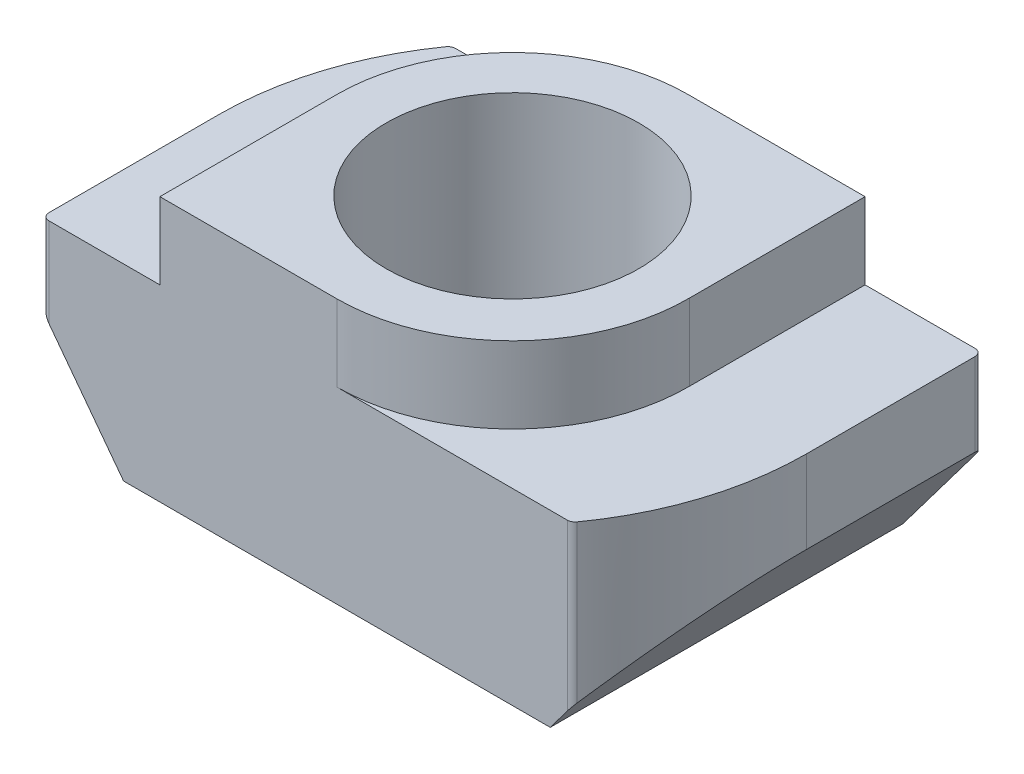
SolidWorks part; units mm, degrees
ref_plane "前视基准面" through (0, 0, 0) normal (0, 0, 1) x (1, 0, 0)
ref_plane "上视基准面" through (0, 0, 0) normal (0, 1, 0) x (1, 0, 0)
ref_plane "右视基准面" through (0, 0, 0) normal (1, 0, 0) x (0, 0, -1)
sketch "草图1" plane through (0, 0, 0) normal (0, 1, 0) x (1, 0, 0)
  line L0 (-6.3587, 0) -> (6.7929, 0) construction
  line L1 (3.92, -3.0123) -> (-4.9005, -3.0123)
  line L2 (4.9795, 0) -> (4.9795, 2.8677)
  line L3 (4.8595, 2.9877) -> (-3.9786, 2.9877)
  line L4 (-5.0205, -2.8923) -> (-5.0205, 0)
  line L6 (4.9795, 2.9877) -> (-5.0205, -3.0123) construction
  line L7 (0, 4.2946) -> (0, -4.2424) construction
  arc A0 (4.0297, -2.956) -> (4.9795, 0) centre (-0.0955, 0) ccw
  arc A1 (4.0297, -2.956) -> (3.92, -3.0123) centre (3.92, -2.8773) cw
  arc A2 (-5.0205, 0) -> (-4.0889, 2.9306) centre (0.0545, 0) cw
  arc A3 (-4.0889, 2.9306) -> (-3.9786, 2.9877) centre (-3.9786, 2.8527) cw
  arc A4 (4.9795, 2.8677) -> (4.8595, 2.9877) centre (4.8595, 2.8677) ccw
  arc A5 (-4.9005, -3.0123) -> (-5.0205, -2.8923) centre (-4.9005, -2.8923) cw
  point P0 (0, 0)
  dimension "D3" = 5.075
  dimension "D4" = 0.135
  dimension "D6" = 5.075
  dimension "D7" = 0.135
  dimension "D8" = 0.12
  dimension "D1" = 10
  dimension "D2" = 6
  dimension "D5" = 3.92
extrude "凸台-拉伸1" add sketch "草图1" along normal blind 3.2
sketch "草图2" plane through (0, 3.2, 0) normal (0, 1, 0) x (1, 0, 0)
  line L1 (0, -3.0123) -> (-3.0123, -3.0123)
  line L2 (2.9877, 0) -> (2.9877, 2.9877)
  line L3 (2.9877, 2.9877) -> (0, 2.9877)
  line L4 (-3.0123, -3.0123) -> (-3.0123, 0)
  line L5 (-4.9005, -3.0123) -> (3.92, -3.0123) construction
  line L6 (2.9877, 2.9877) -> (-3.0123, -3.0123) construction
  line L7 (-6.3112, 0) -> (6.4517, 0) construction
  line L8 (0, -3.8745) -> (0, 3.6707) construction
  line L9 (4.8595, 2.9877) -> (-3.9786, 2.9877) construction
  arc A0 (-3.0123, 0) -> (0, 2.9877) centre (-0.0246, 0) cw
  arc A1 (0, -3.0123) -> (2.9877, 0) centre (0, -0.0246) ccw
  point P0 (0, 0)
  dimension "D1" = 6
extrude "凸台-拉伸2" add sketch "草图2" along normal blind 1.3
sketch "草图3" plane through (0, 0, 0) normal (0, 0, 1) x (1, 0, 0)
  line L0 (5.0205, 0) -> (3.63, 0)
  line L1 (-4.9005, 0) -> (3.92, 0) construction
  line L2 (-3.63, 0) -> (-5.0205, 1.8453)
  line L3 (-5.0205, 3.2) -> (-5.0205, 0) construction
  line L4 (0, -1.7084) -> (0, 1.9848) construction
  line L5 (-5.0205, 1.8453) -> (-5.0205, 0)
  line L6 (-5.0205, 0) -> (-3.63, 0)
  line L7 (5.0205, 1.8453) -> (5.0205, 0)
  line L8 (3.63, 0) -> (5.0205, 1.8453)
  dimension "D1" = 7.26
  dimension "D2" = 53
extrude "切除-拉伸1" cut sketch "草图3" against normal mid plane 9.3
sketch "草图4" plane through (0, 4.5, 0) normal (0, 1, 0) x (1, 0, 0)
  circle A0 centre (-0.0246, 0) radius 2.15
  dimension "D1" = 4.3
extrude "切除-拉伸2" cut sketch "草图4" against normal up to next
cosmetic thread "装饰螺纹线1"
sketch "草图5" [suppressed] plane through (0, 0, 0) normal (0, 1, 0) x (1, 0, 0)
  line L0 (-7.0636, 0) -> (6.9703, 0) construction
  line L1 (3.7417, -3) -> (-4.5, -3)
  line L2 (5, 0) -> (5, 2.5)
  line L3 (4.5, 3) -> (-3.7417, 3)
  line L4 (-5, -2.5) -> (-5, 0)
  line L6 (5, 3) -> (-5, -3) construction
  line L7 (0, 4.4385) -> (0, -4.2975) construction
  arc A0 (4.1574, -2.7778) -> (5, 0) centre (0, 0) ccw
  arc A1 (4.1574, -2.7778) -> (3.7417, -3) centre (3.7417, -2.5) cw
  arc A2 (-5, 0) -> (-4.1574, 2.7778) centre (0, 0) cw
  arc A3 (-4.1574, 2.7778) -> (-3.7417, 3) centre (-3.7417, 2.5) cw
  arc A4 (5, 2.5) -> (4.5, 3) centre (4.5, 2.5) ccw
  arc A5 (-4.5, -3) -> (-5, -2.5) centre (-4.5, -2.5) cw
  point P0 (0, 0)
  dimension "D3" = 5
  dimension "D4" = 0.5
  dimension "D5" = 5
  dimension "D6" = 0.5
  dimension "D7" = 0.5
  dimension "D1" = 10
  dimension "D2" = 6
extrude "凸台-拉伸3" [suppressed] add sketch "草图5" along normal blind 3.2
sketch "草图6" [suppressed] plane through (0, 3.2, 0) normal (0, 1, 0) x (1, 0, 0)
  line L1 (0, -3) -> (-3, -3)
  line L2 (3, 0) -> (3, 3)
  line L3 (3, 3) -> (0, 3)
  line L4 (-3, -3) -> (-3, 0)
  line L5 (4.5, 3) -> (-3.7417, 3) construction
  line L6 (3, 3) -> (-3, -3) construction
  line L7 (-3.3629, 0) -> (3.4229, 0) construction
  line L8 (0, 3.4409) -> (0, -3.4409) construction
  line L9 (-4.5, -3) -> (3.7417, -3) construction
  arc A0 (-3, 0) -> (0, 3) centre (0, 0) cw
  arc A1 (0, -3) -> (3, 0) centre (0, 0) ccw
  point P0 (0, 0)
  dimension "D1" = 6
extrude "凸台-拉伸4" [suppressed] add sketch "草图6" along normal blind 1.3
sketch "草图7" [suppressed] plane through (0, 4.5, 0) normal (0, 1, 0) x (1, 0, 0)
  circle A0 centre (0, 0) radius 1.72
  dimension "D1" = 4.3
extrude "切除-拉伸3" [suppressed] cut sketch "草图7" against normal up to next
cosmetic thread "装饰螺纹线2" [suppressed] parameters "D2"=4
sketch "草图8" [suppressed] plane through (0, 0, 0) normal (0, 0, 1) x (1, 0, 0)
  line L0 (0, -1.0578) -> (0, 1.2542) construction
  line L1 (-5, 2.3679) -> (-3.15, 0)
  line L2 (-5, 3.2) -> (-5, 0) construction
  line L3 (-4.5, 0) -> (3.7417, 0) construction
  line L4 (-3.15, 0) -> (-5, 0)
  line L5 (-5, 0) -> (-5, 2.3679)
  line L6 (5, 0) -> (5, 2.3679)
  line L7 (3.15, 0) -> (5, 0)
  line L8 (5, 2.3679) -> (3.15, 0)
  line L9 (-4.5, 3.2) -> (-5, 3.2) construction
  line L10 (-4.5, 3.2) -> (-5, 3.2)
  line L11 (-5, 3.2) -> (-5, 2.7)
  line L12 (5, 3.2) -> (5, 2.7)
  line L13 (4.5, 3.2) -> (5, 3.2)
  arc A0 (-4.5, 3.2) -> (-5, 2.7) centre (-4.5, 2.7) ccw
  arc A1 (4.5, 3.2) -> (5, 2.7) centre (4.5, 2.7) cw
  dimension "D3" = 0.5
  dimension "D1" = 128
  dimension "D2" = 6.3
extrude "切除-拉伸4" [suppressed] cut sketch "草图8" against normal mid plane 9.3
